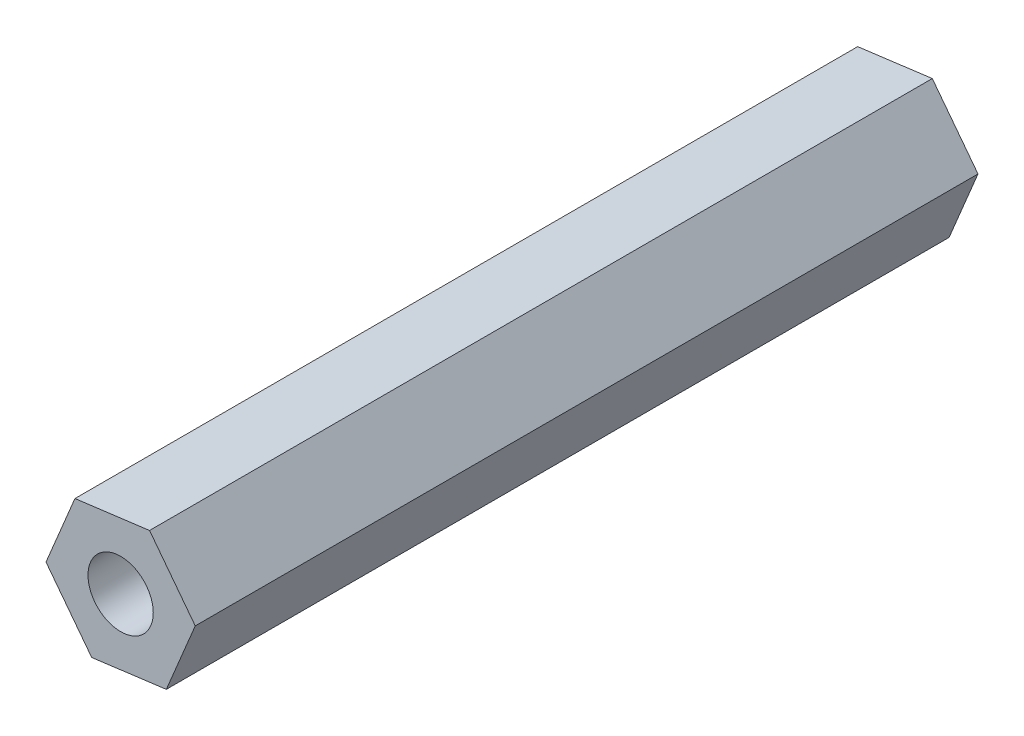
SolidWorks part; units mm, degrees
ref_plane "Front Plane" through (0, 0, 0) normal (0, 0, 1) x (1, 0, 0)
ref_plane "Top Plane" through (0, 0, 0) normal (0, 1, 0) x (1, 0, 0)
ref_plane "Right Plane" through (0, 0, 0) normal (1, 0, 0) x (0, 0, -1)
sketch "Sketch1" plane through (0, 0, 0) normal (0, 0, 1) x (1, 0, 0)
  line L1 (7.2715, 0.9426) -> (2.8194, 6.7686)
  line L2 (2.8194, 6.7686) -> (-4.4521, 5.826)
  line L3 (-4.4521, 5.826) -> (-7.2715, -0.9426)
  line L4 (-7.2715, -0.9426) -> (-2.8194, -6.7686)
  line L5 (-2.8194, -6.7686) -> (4.4521, -5.826)
  line L6 (4.4521, -5.826) -> (7.2715, 0.9426)
  circle A0 centre (0, 0) radius 6.35 construction
  circle A1 centre (0, 0) radius 3.18
extrude "Boss-Extrude1" add sketch "Sketch1" along normal blind 76.27
move or copy body "Body-Move/Copy1" [suppressed] bodies to move or copy 101
